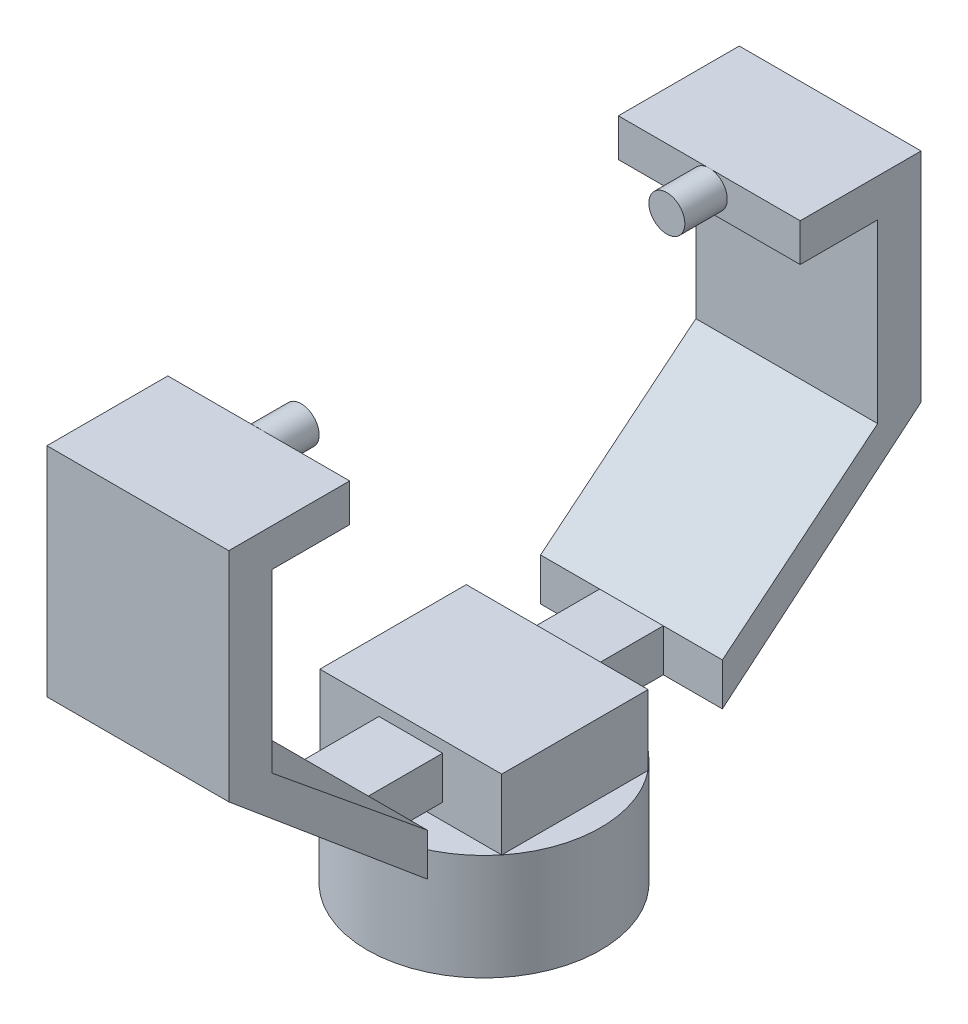
SolidWorks part; units mm, degrees
material "Cast Alloy Steel"
ref_plane "Front Plane" through (0, 0, 0) normal (0, 0, 1) x (1, 0, 0)
ref_plane "Top Plane" through (0, 0, 0) normal (0, 1, 0) x (1, 0, 0)
ref_plane "Right Plane" through (0, 0, 0) normal (1, 0, 0) x (0, 0, -1)
sketch "Sketch1" plane through (0, 0, 0) normal (0, 1, 0) x (1, 0, 0)
  circle A0 centre (0, 0) radius 550
  dimension "D1" = 1100
extrude "Base" add sketch "Sketch1" along normal blind 500
sketch "Sketch2" plane through (0, 500, 0) normal (0, 1, 0) x (1, 0, 0)
  line L1 (-428.4022, 344.9225) -> (428.4022, 344.9225)
  line L2 (-428.4022, 344.9225) -> (-428.4022, -344.9225)
  line L3 (-428.4022, -344.9225) -> (428.4022, -344.9225)
  line L4 (428.4022, 344.9225) -> (428.4022, -344.9225)
  circle A0 centre (0, 0) radius 550 construction
extrude "Arm Connection Point" add sketch "Sketch2" along normal blind 330 contours L2 L1 L4 L3
sketch "Sketch3" plane through (0, 0, 344.9225) normal (0, 0, 1) x (1, 0, 0)
  line L1 (-150, 776.0312) -> (150, 776.0312)
  line L2 (-150, 776.0312) -> (-150, 576.0312)
  line L3 (-150, 576.0312) -> (150, 576.0312)
  line L4 (150, 776.0312) -> (150, 576.0312)
  point P4 (0, 776.0312)
  dimension "D1" = 200
  dimension "D2" = 300
extrude "Arm Base" add sketch "Sketch3" along normal blind 350
sketch "Sketch4" plane through (-428.4022, 0, 0) normal (-1, 0, 0) x (0, 0, 1)
  line L0 (694.9225, 776.0312) -> (694.9225, 576.0312)
  line L1 (694.9225, 576.0312) -> (1631.2288, 1359.8195)
  line L2 (1631.2288, 1359.8195) -> (1631.2288, 2384.9013)
  line L3 (1631.2288, 2384.9013) -> (1061.5967, 2384.9013)
  line L4 (1061.5967, 2384.9013) -> (1061.5967, 2206.1564)
  line L5 (1061.5967, 2206.1564) -> (1426.6422, 2206.1564)
  line L6 (1426.6422, 2206.1564) -> (1426.6422, 1374.5174)
  line L7 (1426.6422, 1374.5174) -> (694.9225, 776.0312)
extrude "Arm" add sketch "Sketch4" against normal up to surface (856.8044 mm away) up to face at (428.4022, 665, 0)
mirror "Mirror1" about plane through (0, 0, 0) normal (0, 0, 1) of "Arm Base", "Arm"
sketch "Sketch5" plane through (0, 0, 1061.5967) normal (0, 0, -1) x (-1, 0, 0)
  line L0 (0, 456.5) -> (0, -456.5) construction
  circle A0 centre (0, 2300.9641) radius 84.8193
extrude "Arm Connection to Light" add sketch "Sketch5" along normal blind 200
mirror "Mirror2" about plane through (0, 0, 0) normal (0, 0, 1) of "Arm Connection to Light"
